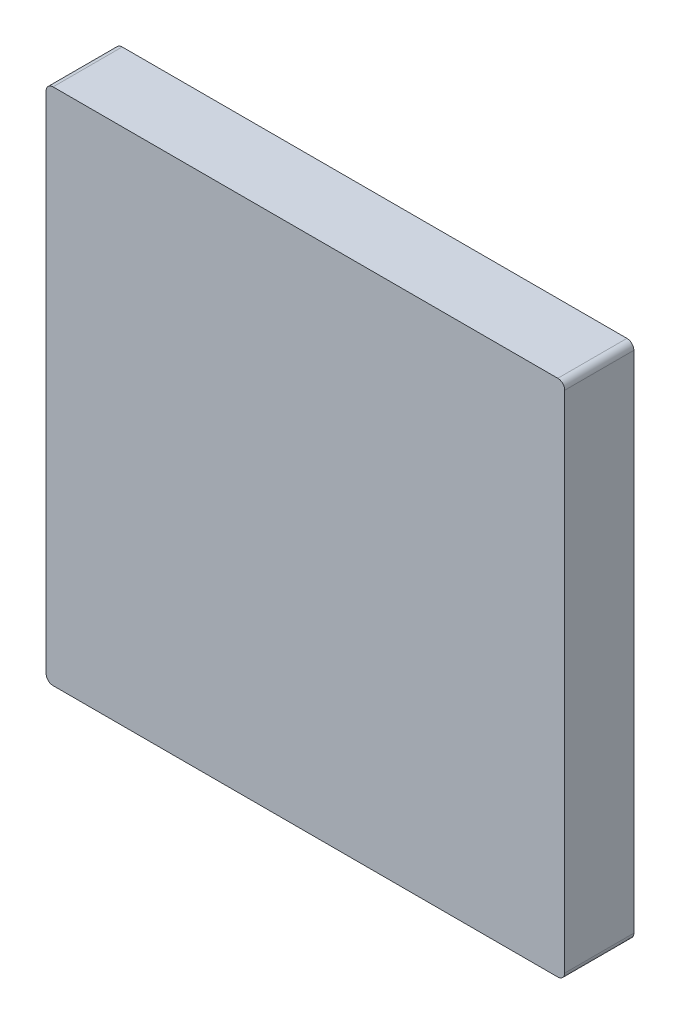
SolidWorks part; units mm, degrees
ref_plane "Front Plane" through (0, 0, 0) normal (0, 0, 1) x (1, 0, 0)
ref_plane "Top Plane" through (0, 0, 0) normal (0, 1, 0) x (1, 0, 0)
ref_plane "Right Plane" through (0, 0, 0) normal (1, 0, 0) x (0, 0, -1)
sketch "Sketch2" plane through (0, 0, 0) normal (0, 0, 1) x (1, 0, 0)
  line L1 (-75, -75) -> (75, -75)
  line L2 (-75, -75) -> (-75, 75)
  line L3 (-75, 75) -> (75, 75)
  line L4 (75, -75) -> (75, 75)
  line L5 (-75, -75) -> (75, 75) construction
  line L6 (-75, 75) -> (75, -75) construction
  point P0 (0, 0)
extrude "Boss-Extrude1" add sketch "Sketch2" along normal blind 20
fillet "Fillet1" radius 2 4 edges at (-75, -75, 10) (75, -75, 10) (-75, 75, 10) (75, 75, 10)
